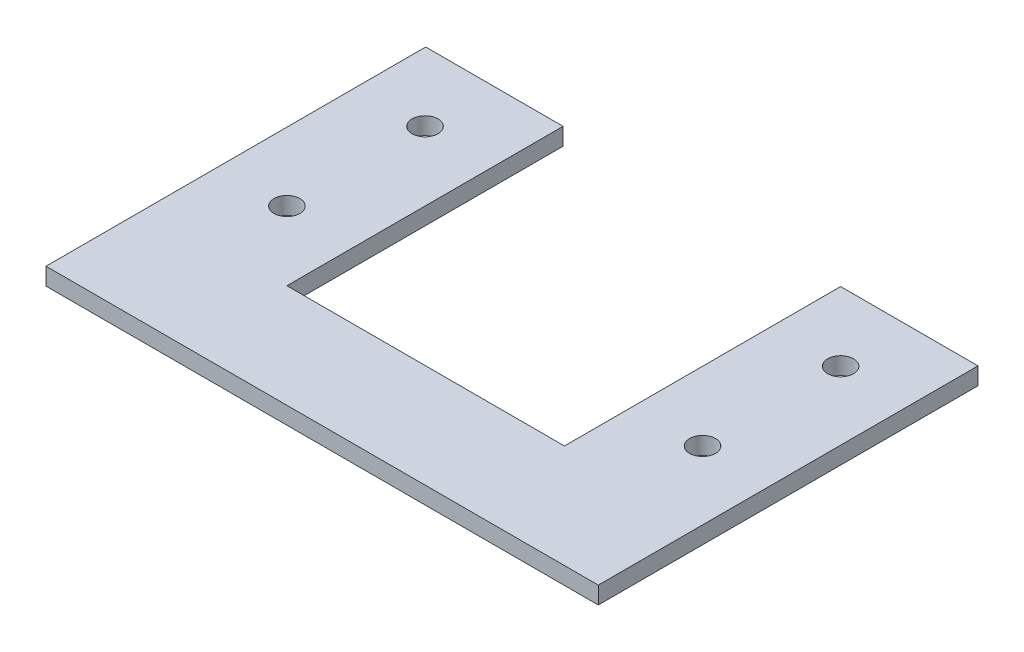
SolidWorks part; units mm, degrees
ref_plane "Front Plane" through (0, 0, 0) normal (0, 0, 1) x (1, 0, 0)
ref_plane "Top Plane" through (0, 0, 0) normal (0, 1, 0) x (1, 0, 0)
ref_plane "Right Plane" through (0, 0, 0) normal (1, 0, 0) x (0, 0, -1)
sketch "Sketch1" plane through (0, 0, 0) normal (0, 1, 0) x (1, 0, 0)
  line L0 (0, 34.925) -> (0, 0) construction
  line L1 (-50.8, 34.925) -> (50.8, 34.925)
  line L2 (-50.8, 34.925) -> (-50.8, -34.925)
  line L3 (-50.8, -34.925) -> (50.8, -34.925)
  line L4 (50.8, 34.925) -> (50.8, -34.925)
  line L5 (-50.8, 34.925) -> (50.8, -34.925) construction
  line L6 (-50.8, -34.925) -> (50.8, 34.925) construction
  line L7 (-25.527, 34.925) -> (25.527, 34.925)
  line L8 (-25.527, 34.925) -> (-25.527, -15.875)
  line L9 (-25.527, -15.875) -> (25.527, -15.875)
  line L10 (25.527, 34.925) -> (25.527, -15.875)
  circle A0 centre (-38.227, 22.225) radius 2.3812
  circle A1 centre (-38.227, -3.175) radius 2.3812
  circle A2 centre (38.227, -3.175) radius 2.3812
  circle A3 centre (38.227, 22.225) radius 2.3812
  point P0 (0, 0)
  point P16 (0, 0)
  dimension "D8" = 4.7625
  dimension "D9" = 4.7625
  dimension "D1" = 101.6
  dimension "D2" = 51.054
  dimension "D3" = 25.527
  dimension "D4" = 50.8
  dimension "D5" = 69.85
  dimension "D6" = 12.7
  dimension "D7" = 25.4
  dimension "D10" = 12.7
extrude "Boss-Extrude1" add sketch "Sketch1" along normal blind 3.175 contours L1 L10 L9 L8 L2 L3 L4 A2 A1 A0 A3
